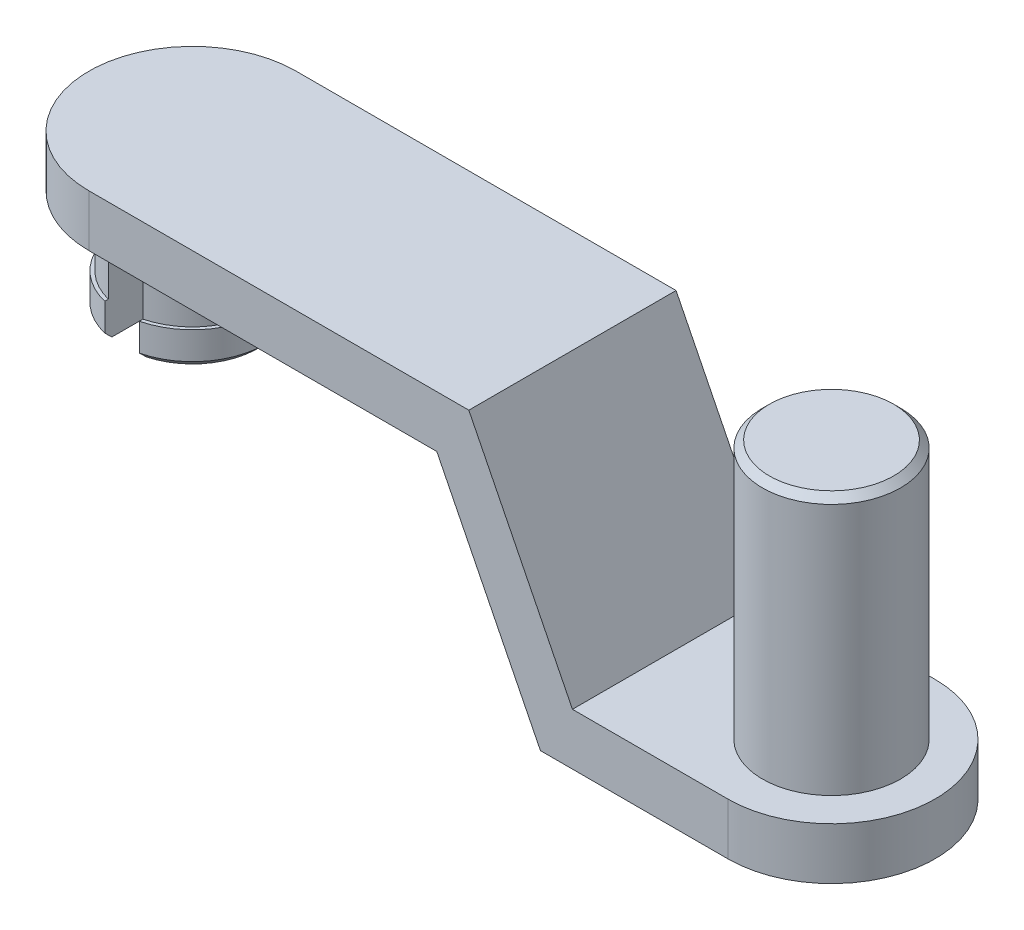
SolidWorks part; units mm, degrees
ref_plane "前视基准面" through (0, 0, 0) normal (0, 0, 1) x (1, 0, 0)
ref_plane "上视基准面" through (0, 0, 0) normal (0, 1, 0) x (1, 0, 0)
ref_plane "右视基准面" through (0, 0, 0) normal (1, 0, 0) x (0, 0, -1)
sketch "草图1" plane through (0, 0, 0) normal (0, 0, 1) x (1, 0, 0)
  line L0 (0, 0) -> (11, 0)
  line L1 (11, 0) -> (14, -6)
  line L2 (14, -6) -> (18.5, -6)
  line L3 (0, -1.5) -> (10.0729, -1.5)
  line L4 (10.0729, -1.5) -> (13.0729, -7.5)
  line L5 (13.0729, -7.5) -> (18.5, -7.5)
  line L6 (0, 0) -> (0, -1.5)
  line L7 (18.5, -6) -> (18.5, -7.5)
  dimension "D1" = 11
  dimension "D2" = 3
  dimension "D3" = 6
  dimension "D4" = 4.5
  dimension "D5" = 1.5
extrude "凸台-拉伸1" add sketch "草图1" along normal blind 6
sketch "草图2" plane through (0, 0, 0) normal (0, 1, 0) x (1, 0, 0)
  line L0 (0, -6) -> (0, 0) construction
  circle A0 centre (0, -3) radius 3
extrude "凸台-拉伸2" add sketch "草图2" against normal blind 1.5
sketch "草图3" plane through (0, -6, 0) normal (0, 1, 0) x (1, 0, 0)
  line L0 (18.5, -6) -> (18.5, 0) construction
  circle A0 centre (18.5, -3) radius 3
extrude "凸台-拉伸3" add sketch "草图3" against normal blind 1.5
sketch "草图4" plane through (0, -1.5, 0) normal (0, -1, 0) x (1, 0, 0)
  circle A0 centre (0, 3) radius 2
  dimension "D1" = 4
extrude "凸台-拉伸4" add sketch "草图4" along normal blind 2
sketch "草图5" plane through (0, -3.5, 0) normal (0, -1, 0) x (1, 0, 0)
  circle A0 centre (0, 3) radius 2.1
  dimension "D1" = 4.2
extrude "凸台-拉伸5" add sketch "草图5" along normal blind 1
chamfer "倒角1" distance 0.2 angle 45 1 edges at (0, -4.5, 0.9)
sketch "草图6" plane through (0, -4.5, 0) normal (0, -1, 0) x (1, 0, 0)
  line L0 (0.5, 5.5) -> (0.5, 0.5)
  line L1 (0.5, 5.5) -> (-0.5, 5.5)
  line L2 (0.5, 0.5) -> (-0.5, 0.5)
  line L3 (-0.5, 5.5) -> (-0.5, 0.5)
  line L4 (0.5, 5.5) -> (-0.5, 0.5) construction
  line L5 (0.5, 0.5) -> (-0.5, 5.5) construction
  point P1 (0, 3)
  dimension "D1" = 1
  dimension "D2" = 5
extrude "切除-拉伸1" cut sketch "草图6" against normal blind 2
sketch "草图7" plane through (0, -6, 0) normal (0, 1, 0) x (1, 0, 0)
  circle A0 centre (18.5, -3) radius 2
  dimension "D1" = 4
extrude "凸台-拉伸6" add sketch "草图7" along normal blind 7.5
chamfer "倒角2" distance 0.2 angle 45 1 edges at (16.5, 1.5, 3)
